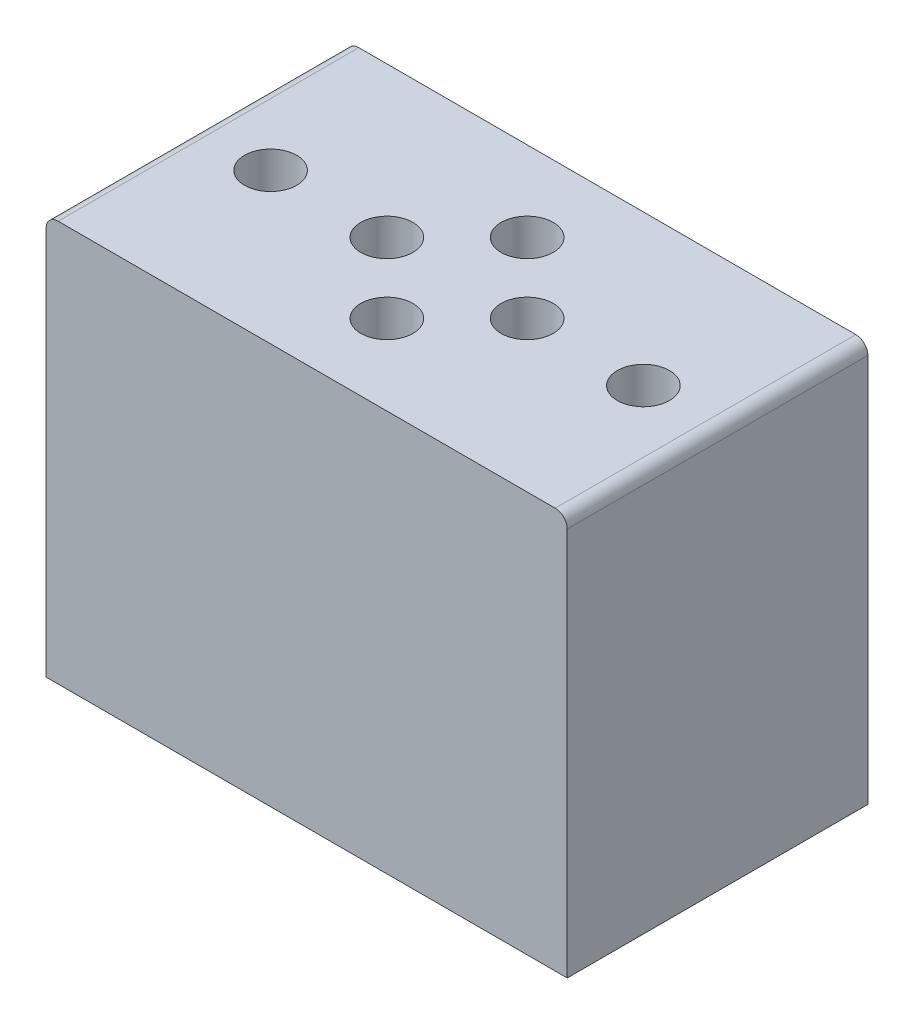
SolidWorks part; units mm, degrees
ref_plane "前视基准面" through (0, 0, 0) normal (0, 0, 1) x (1, 0, 0)
ref_plane "上视基准面" through (0, 0, 0) normal (0, 1, 0) x (1, 0, 0)
ref_plane "右视基准面" through (0, 0, 0) normal (1, 0, 0) x (0, 0, -1)
sketch "Sketch1" plane through (0, 0, 0) normal (0, 0, 1) x (1, 0, 0)
  line L1 (-33.4969, 14.6468) -> (16.1031, 14.6468)
  line L2 (-34.6969, 13.4468) -> (-34.6969, -25.3532)
  line L3 (-34.6969, -25.3532) -> (17.3031, -25.3532)
  line L4 (17.3031, 13.4468) -> (17.3031, -25.3532)
  arc A0 (16.1031, 14.6468) -> (17.3031, 13.4468) centre (16.1031, 13.4468) cw
  arc A1 (-33.4969, 14.6468) -> (-34.6969, 13.4468) centre (-33.4969, 13.4468) ccw
  point P6 (17.3031, 14.6468)
  point P9 (-34.6969, 14.6468)
  dimension "D3" = 1.2
  dimension "D1" = 52
  dimension "D2" = 40
extrude "Boss-Extrude1" add sketch "Sketch1" against normal blind 20
sketch "Sketch2" plane through (0, 0, 0) normal (0, 0, 1) x (1, 0, 0)
  line L0 (16.1031, 14.6468) -> (-33.4969, 14.6468) construction
  circle A0 centre (-8.6969, -5.3532) radius 6.6
  dimension "D1" = 13.2
  dimension "D2" = 20
sketch "Sketch3" plane through (0, 0, 0) normal (0, 0, 1) x (1, 0, 0)
  line L4 (17.3031, -25.3532) -> (17.3031, 13.4468)
  line L5 (16.1031, 14.6468) -> (-33.4969, 14.6468)
  line L6 (-34.6969, 13.4468) -> (-34.6969, -25.3532)
  line L7 (-34.6969, -25.3532) -> (17.3031, -25.3532)
  line L8 (17.3031, -25.3532) -> (17.3031, 13.4468)
  line L9 (16.1031, 14.6468) -> (-33.4969, 14.6468)
  line L10 (-34.6969, 13.4468) -> (-34.6969, -25.3532)
  line L11 (-34.6969, -25.3532) -> (17.3031, -25.3532)
  arc A2 (17.3031, 13.4468) -> (16.1031, 14.6468) centre (16.1031, 13.4468) ccw
  arc A3 (-33.4969, 14.6468) -> (-34.6969, 13.4468) centre (-33.4969, 13.4468) ccw
  arc A4 (17.3031, 13.4468) -> (16.1031, 14.6468) centre (16.1031, 13.4468) ccw
  arc A5 (-33.4969, 14.6468) -> (-34.6969, 13.4468) centre (-33.4969, 13.4468) ccw
  dimension "D1" = 0
extrude "Boss-Extrude2" add sketch "Sketch3" along normal blind 10
ref_plane "Plane1" through (0, 0, -5) normal (0, 0, -1) x (-1, 0, 0)
sketch "Sketch4" plane through (0, 14.6468, 0) normal (0, 1, 0) x (1, 0, 0)
  circle A12 centre (-27.2969, 5) radius 2.6
  circle A13 centre (-15.6969, 5) radius 2.6
  circle A14 centre (-8.6969, 12) radius 2.6
  circle A15 centre (-8.6969, -2) radius 2.6
  circle A16 centre (-1.6969, 5) radius 2.6
  circle A17 centre (9.9031, 5) radius 2.6
  dimension "D1" = 5.2
extrude "Cut-Extrude2" cut sketch "Sketch4" against normal blind 6
extrude "Cut-Extrude3" cut sketch "Sketch2" against normal up to next
